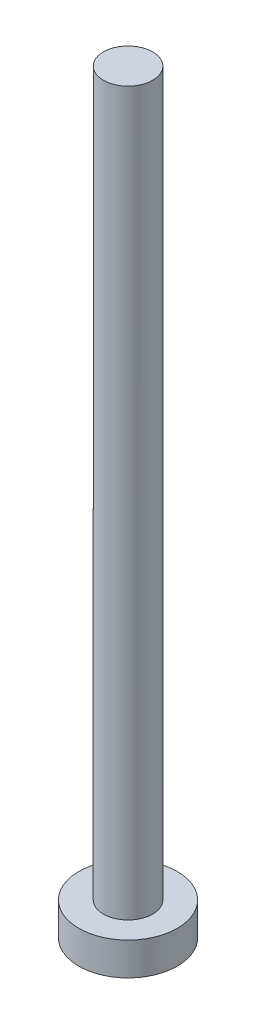
SolidWorks part; units mm, degrees
ref_plane "Front Plane" through (0, 0, 0) normal (0, 0, 1) x (1, 0, 0)
ref_plane "Top Plane" through (0, 0, 0) normal (0, 1, 0) x (1, 0, 0)
ref_plane "Right Plane" through (0, 0, 0) normal (1, 0, 0) x (0, 0, -1)
sketch "Sketch1" plane through (0, 0, 0) normal (0, 1, 0) x (1, 0, 0)
  circle A0 centre (0, 0) radius 1.5
  dimension "D1" = 3
extrude "Boss-Extrude1" add sketch "Sketch1" along normal blind 46
sketch "Sketch2" plane through (0, 0, 0) normal (0, -1, 0) x (1, 0, 0)
  circle A0 centre (0, 0) radius 3
  dimension "D1" = 6
extrude "Boss-Extrude2" add sketch "Sketch2" against normal blind 2
